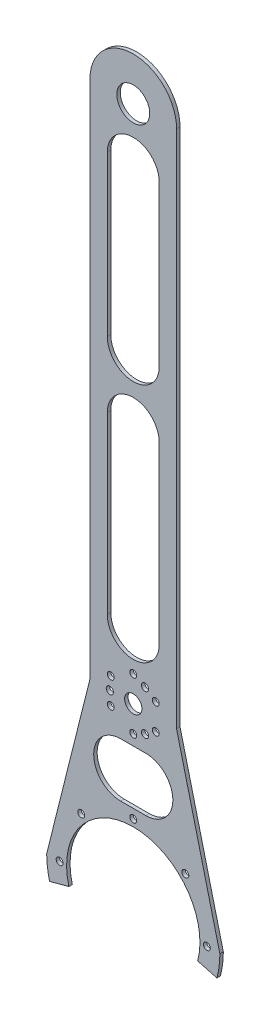
SolidWorks part; units mm, degrees
ref_plane "前视基准面" through (0, 0, 0) normal (0, 0, 1) x (1, 0, 0)
ref_plane "上视基准面" through (0, 0, 0) normal (0, 1, 0) x (1, 0, 0)
ref_plane "右视基准面" through (0, 0, 0) normal (1, 0, 0) x (0, 0, -1)
sketch "草图1" plane through (0, 0, 0) normal (0, 0, 1) x (1, 0, 0)
  line L0 (0, 0) -> (0, -100) construction
  line L1 (-50, 0) -> (-50, -100) construction
  line L2 (50, 0) -> (50, -100) construction
  line L3 (0, -100) -> (-48.2963, -112.941) construction
  line L4 (0, -100) -> (-38.5, -100) construction
  line L5 (0, -100) -> (42.5, -100) construction
  line L6 (0, -100) -> (41.0518, -110.9998) construction
  line L7 (37.1881, -109.9645) -> (48.2963, -112.941)
  line L8 (-48.2963, -112.941) -> (-37.1881, -109.9645)
  line L9 (-25, 0) -> (-50, -100)
  line L10 (25, 0) -> (50, -100)
  line L11 (0, 0) -> (0, 300) construction
  line L12 (-25, 300) -> (-25, 0)
  line L13 (25, 0) -> (25, 300)
  line L14 (0, 37.2318) -> (0, 138.1902) construction
  line L15 (-15, 37.2318) -> (-15, 138.1902)
  line L16 (15, 37.2318) -> (15, 138.1902)
  line L17 (-7.2858, -36.6834) -> (7.2858, -36.6834) construction
  line L18 (-7.2858, -21.1152) -> (7.2858, -21.1152)
  line L19 (-7.2858, -52.2515) -> (7.2858, -52.2515)
  line L20 (0, 176.1443) -> (0, 268.2878) construction
  line L21 (-15, 176.1443) -> (-15, 268.2878)
  line L22 (15, 176.1443) -> (15, 268.2878)
  circle A0 centre (0, 0) radius 15 construction
  circle A1 centre (0, 0) radius 13.53 construction
  circle A2 centre (0, -15) radius 2
  circle A3 centre (-12.9904, -7.5) radius 2
  circle A4 centre (-12.9904, 7.5) radius 2
  circle A5 centre (0, 15) radius 2
  circle A6 centre (12.9904, 7.5) radius 2
  circle A7 centre (12.9904, -7.5) radius 2
  circle A8 centre (-13.53, 0) radius 2.08
  circle A9 centre (6.765, 11.7173) radius 2.08
  circle A10 centre (6.765, -11.7173) radius 2.08
  circle A11 centre (0, 0) radius 5
  circle A12 centre (0, 0) radius 50 construction
  circle A13 centre (0, -100) radius 42.5 construction
  circle A14 centre (0, -142.5) radius 2 construction
  circle A15 centre (-30.052, -130.052) radius 2 construction
  circle A16 centre (-42.5, -100) radius 2
  circle A17 centre (-30.052, -69.948) radius 2
  circle A18 centre (0, -57.5) radius 2
  circle A19 centre (30.052, -69.948) radius 2
  circle A20 centre (42.5, -100) radius 2
  circle A21 centre (30.052, -130.052) radius 2 construction
  circle A22 centre (0, -100) radius 38.5 construction
  arc A24 (-50, -100) -> (50, -100) centre (0, -100) ccw construction
  arc A25 (-50, 0) -> (50, 0) centre (0, 0) cw construction
  arc A26 (-37.1881, -109.9645) -> (37.1881, -109.9645) centre (0, -100) cw
  arc A27 (-50, -100) -> (-48.2963, -112.941) centre (0, -100) ccw
  arc A28 (50, -100) -> (48.2963, -112.941) centre (0, -100) cw
  circle A29 centre (0, 0) radius 25 construction
  arc A30 (-25, 0) -> (25, 0) centre (0, 0) cw construction
  circle A31 centre (0, 300) radius 9.5
  arc A33 (-15, 37.2318) -> (15, 37.2318) centre (0, 37.2318) ccw
  arc A34 (15, 138.1902) -> (-15, 138.1902) centre (0, 138.1902) ccw
  arc A35 (-7.2858, -21.1152) -> (-7.2858, -52.2515) centre (-7.2858, -36.6834) ccw
  arc A36 (7.2858, -52.2515) -> (7.2858, -21.1152) centre (7.2858, -36.6834) ccw
  arc A37 (-25, 300) -> (25, 300) centre (0, 300) cw
  arc A38 (-15, 176.1443) -> (15, 176.1443) centre (0, 176.1443) ccw
  arc A39 (15, 268.2878) -> (-15, 268.2878) centre (0, 268.2878) ccw
  point P62 (0, 207.3871)
  point P66 (0, 87.711)
  point P73 (0, -36.6834)
  point P78 (0, 154.3617)
  point P80 (0, 222.216)
  point P87 (0, 194.4767)
  point P88 (0, 0)
  point P89 (0, 0)
  point P90 (0, 176.1443)
  point P91 (0, 138.1902)
  dimension "D1" = 8
  dimension "D2" = 15
  dimension "D3" = 15
extrude "凸台-拉伸1" add sketch "草图1" along normal blind 2 contours A12
